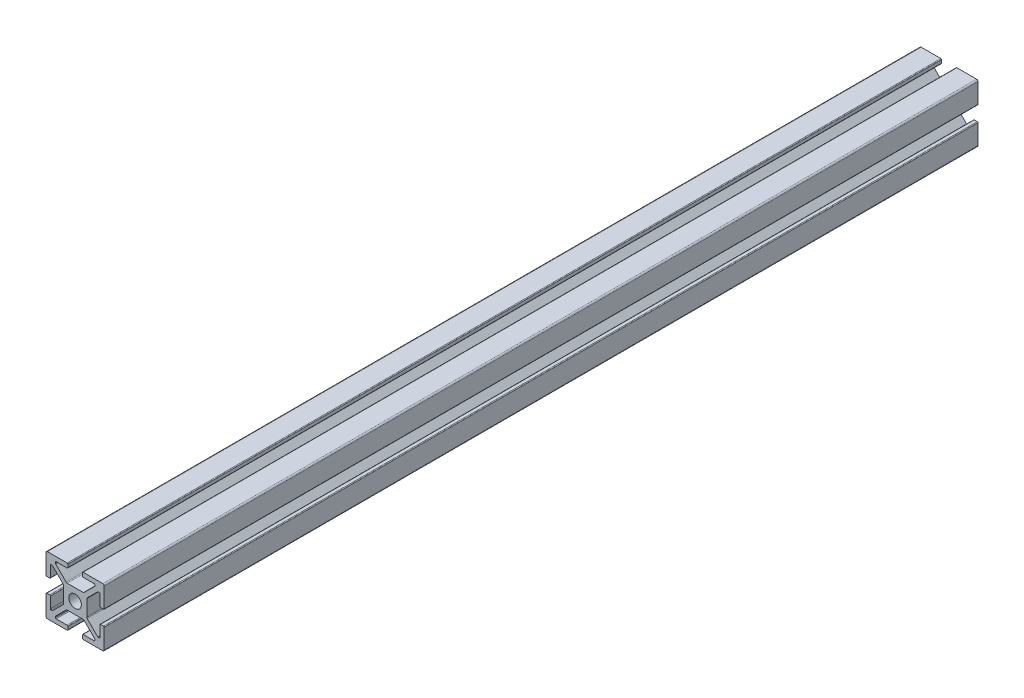
SolidWorks part; units mm, degrees
ref_plane "Спереди" through (0, 0, 0) normal (0, 0, 1) x (1, 0, 0)
ref_plane "Сверху" through (0, 0, 0) normal (0, 1, 0) x (1, 0, 0)
ref_plane "Справа" through (0, 0, 0) normal (1, 0, 0) x (0, 0, -1)
sketch "Эскиз1" plane through (0, 0, 0) normal (0, 0, 1) x (1, 0, 0)
  line L0 (-10, -2.75) -> (-10, -9.5)
  line L1 (-9.5, -10) -> (-2.75, -10)
  line L2 (-2.5, -9.75) -> (-2.5, -8.75)
  line L3 (-2.75, -8.5) -> (-6.5, -8.5)
  line L4 (-6.75, -8.25) -> (-6.75, -7.9142)
  line L5 (-6.6768, -7.7374) -> (-3.0858, -4.1464)
  line L6 (-2.7322, -4) -> (2.7322, -4)
  line L7 (3.0858, -4.1464) -> (6.6768, -7.7374)
  line L8 (6.75, -7.9142) -> (6.75, -8.25)
  line L9 (6.5, -8.5) -> (2.75, -8.5)
  line L10 (2.5, -8.75) -> (2.5, -9.75)
  line L11 (2.75, -10) -> (9.5, -10)
  line L12 (10, -9.5) -> (10, -2.75)
  line L13 (9.75, -2.5) -> (8.75, -2.5)
  line L14 (8.5, -2.75) -> (8.5, -6.5)
  line L15 (8.25, -6.75) -> (7.9142, -6.75)
  line L16 (7.7374, -6.6768) -> (4.1464, -3.0858)
  line L17 (4, -2.7322) -> (4, 2.7322)
  line L18 (4.1464, 3.0858) -> (7.7374, 6.6768)
  line L19 (7.9142, 6.75) -> (8.25, 6.75)
  line L20 (8.5, 6.5) -> (8.5, 2.75)
  line L21 (8.75, 2.5) -> (9.75, 2.5)
  line L22 (10, 2.75) -> (10, 9.5)
  line L23 (9.5, 10) -> (2.75, 10)
  line L24 (2.5, 9.75) -> (2.5, 8.75)
  line L25 (2.75, 8.5) -> (6.5, 8.5)
  line L26 (6.75, 8.25) -> (6.75, 7.8107)
  line L27 (6.75, 7.8107) -> (3.0126, 4.0732)
  line L28 (2.8358, 4) -> (-2.7322, 4)
  line L29 (-3.0858, 4.1464) -> (-6.6768, 7.7374)
  line L30 (-6.75, 7.9142) -> (-6.75, 8.25)
  line L31 (-6.5, 8.5) -> (-2.75, 8.5)
  line L32 (-2.5, 8.75) -> (-2.5, 9.75)
  line L33 (-2.75, 10) -> (-9.5, 10)
  line L34 (-10, 9.5) -> (-10, 2.75)
  line L35 (-9.75, 2.5) -> (-8.75, 2.5)
  line L36 (-8.5, 2.75) -> (-8.5, 6.5)
  line L37 (-8.25, 6.75) -> (-7.9142, 6.75)
  line L38 (-7.7374, 6.6768) -> (-4.1464, 3.0858)
  line L39 (-4, 2.7322) -> (-4, -2.7322)
  line L40 (-4.1464, -3.0858) -> (-7.7374, -6.6768)
  line L41 (-7.9142, -6.75) -> (-8.25, -6.75)
  line L42 (-8.5, -6.5) -> (-8.5, -2.75)
  line L43 (-8.75, -2.5) -> (-9.75, -2.5)
  circle A0 centre (0, 0) radius 2.15
  arc A1 (-10, -9.5) -> (-9.5, -10) centre (-9.5, -9.5) ccw
  arc A2 (-2.75, -10) -> (-2.5, -9.75) centre (-2.75, -9.75) ccw
  arc A3 (-2.5, -8.75) -> (-2.75, -8.5) centre (-2.75, -8.75) ccw
  arc A4 (-6.5, -8.5) -> (-6.75, -8.25) centre (-6.5, -8.25) cw
  arc A5 (-6.75, -7.9142) -> (-6.6768, -7.7374) centre (-6.5, -7.9142) cw
  arc A6 (-3.0858, -4.1464) -> (-2.7322, -4) centre (-2.7322, -4.5) cw
  arc A7 (2.7322, -4) -> (3.0858, -4.1464) centre (2.7322, -4.5) cw
  arc A8 (6.6768, -7.7374) -> (6.75, -7.9142) centre (6.5, -7.9142) cw
  arc A9 (6.75, -8.25) -> (6.5, -8.5) centre (6.5, -8.25) cw
  arc A10 (2.75, -8.5) -> (2.5, -8.75) centre (2.75, -8.75) ccw
  arc A11 (2.5, -9.75) -> (2.75, -10) centre (2.75, -9.75) ccw
  arc A12 (9.5, -10) -> (10, -9.5) centre (9.5, -9.5) ccw
  arc A13 (10, -2.75) -> (9.75, -2.5) centre (9.75, -2.75) ccw
  arc A14 (8.75, -2.5) -> (8.5, -2.75) centre (8.75, -2.75) ccw
  arc A15 (8.5, -6.5) -> (8.25, -6.75) centre (8.25, -6.5) cw
  arc A16 (7.9142, -6.75) -> (7.7374, -6.6768) centre (7.9142, -6.5) cw
  arc A17 (4.1464, -3.0858) -> (4, -2.7322) centre (4.5, -2.7322) cw
  arc A18 (4, 2.7322) -> (4.1464, 3.0858) centre (4.5, 2.7322) cw
  arc A19 (7.7374, 6.6768) -> (7.9142, 6.75) centre (7.9142, 6.5) cw
  arc A20 (8.25, 6.75) -> (8.5, 6.5) centre (8.25, 6.5) cw
  arc A21 (8.5, 2.75) -> (8.75, 2.5) centre (8.75, 2.75) ccw
  arc A22 (9.75, 2.5) -> (10, 2.75) centre (9.75, 2.75) ccw
  arc A23 (10, 9.5) -> (9.5, 10) centre (9.5, 9.5) ccw
  arc A24 (2.75, 10) -> (2.5, 9.75) centre (2.75, 9.75) ccw
  arc A25 (2.5, 8.75) -> (2.75, 8.5) centre (2.75, 8.75) ccw
  arc A26 (6.5, 8.5) -> (6.75, 8.25) centre (6.5, 8.25) cw
  arc A27 (3.0126, 4.0732) -> (2.8358, 4) centre (2.8358, 4.25) cw
  arc A28 (-2.7322, 4) -> (-3.0858, 4.1464) centre (-2.7322, 4.5) cw
  arc A29 (-6.6768, 7.7374) -> (-6.75, 7.9142) centre (-6.5, 7.9142) cw
  arc A30 (-6.75, 8.25) -> (-6.5, 8.5) centre (-6.5, 8.25) cw
  arc A31 (-2.75, 8.5) -> (-2.5, 8.75) centre (-2.75, 8.75) ccw
  arc A32 (-2.5, 9.75) -> (-2.75, 10) centre (-2.75, 9.75) ccw
  arc A33 (-9.5, 10) -> (-10, 9.5) centre (-9.5, 9.5) ccw
  arc A34 (-10, 2.75) -> (-9.75, 2.5) centre (-9.75, 2.75) ccw
  arc A35 (-8.75, 2.5) -> (-8.5, 2.75) centre (-8.75, 2.75) ccw
  arc A36 (-8.5, 6.5) -> (-8.25, 6.75) centre (-8.25, 6.5) cw
  arc A37 (-7.9142, 6.75) -> (-7.7374, 6.6768) centre (-7.9142, 6.5) cw
  arc A38 (-4.1464, 3.0858) -> (-4, 2.7322) centre (-4.5, 2.7322) cw
  arc A39 (-4, -2.7322) -> (-4.1464, -3.0858) centre (-4.5, -2.7322) cw
  arc A40 (-7.7374, -6.6768) -> (-7.9142, -6.75) centre (-7.9142, -6.5) cw
  arc A41 (-8.25, -6.75) -> (-8.5, -6.5) centre (-8.25, -6.5) cw
  arc A42 (-8.5, -2.75) -> (-8.75, -2.5) centre (-8.75, -2.75) ccw
  arc A43 (-9.75, -2.5) -> (-10, -2.75) centre (-9.75, -2.75) ccw
extrude "Бобышка-Вытянуть1" add sketch "Эскиз1" against normal blind 300
